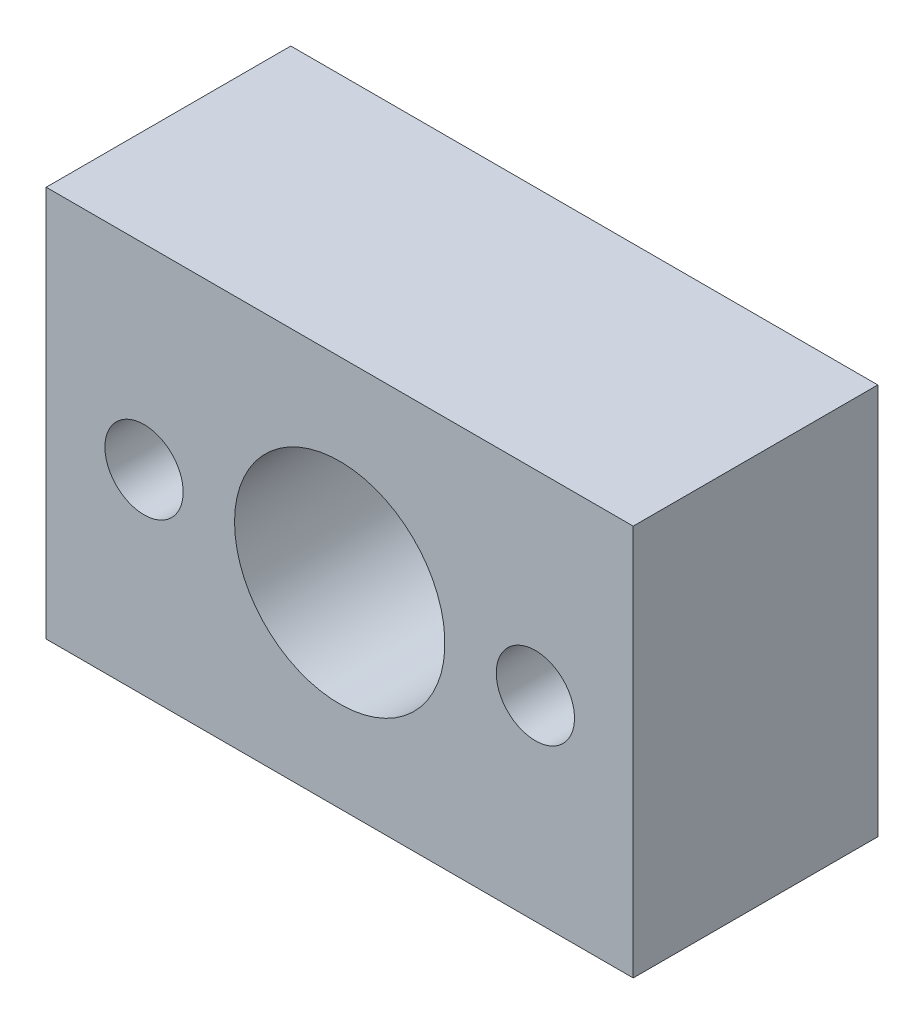
SolidWorks part; units mm, degrees
ref_plane "Front Plane" through (0, 0, 0) normal (0, 0, 1) x (1, 0, 0)
ref_plane "Top Plane" through (0, 0, 0) normal (0, 1, 0) x (1, 0, 0)
ref_plane "Right Plane" through (0, 0, 0) normal (1, 0, 0) x (0, 0, -1)
sketch "Sketch1" plane through (0, 0, 0) normal (0, 0, 1) x (1, 0, 0)
  line L1 (-12, -8) -> (12, -8)
  line L2 (-12, -8) -> (-12, 8)
  line L3 (-12, 8) -> (12, 8)
  line L4 (12, -8) -> (12, 8)
extrude "Boss-Extrude1" add sketch "Sketch1" along normal blind 10
sketch "Sketch2" plane through (0, 0, 0) normal (0, 0, 1) x (1, 0, 0)
  circle A0 centre (0, 0) radius 4.3
  circle A1 centre (8, 0) radius 1.6
  circle A2 centre (-8, 0) radius 1.6
extrude "Cut-Extrude2" cut sketch "Sketch2" along normal blind 11
